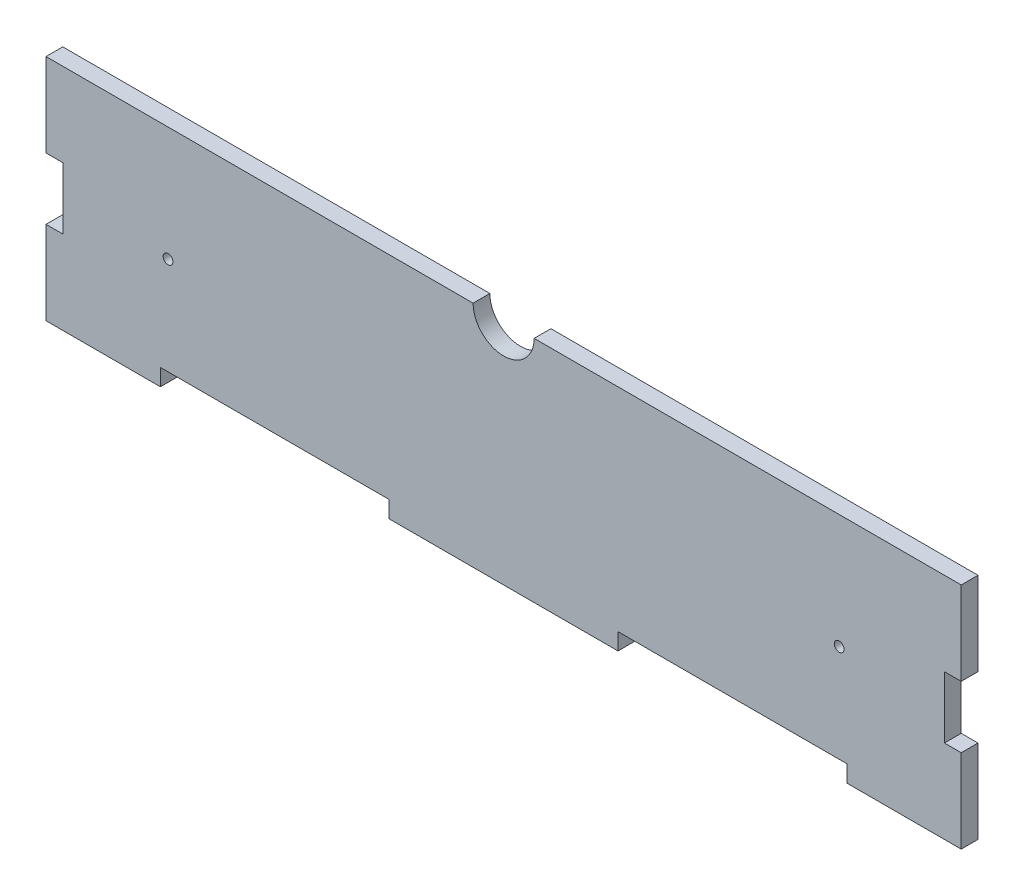
SolidWorks part; units mm, degrees
ref_plane "Front Plane" through (0, 0, 0) normal (0, 0, 1) x (1, 0, 0)
ref_plane "Top Plane" through (0, 0, 0) normal (0, 1, 0) x (1, 0, 0)
ref_plane "Right Plane" through (0, 0, 0) normal (1, 0, 0) x (0, 0, -1)
sketch "Sketch1" plane through (0, 0, 0) normal (0, 0, 1) x (1, 0, 0)
  line L0 (0, 78) -> (0, 50.625)
  line L1 (0, 50.625) -> (5.5, 50.625)
  line L2 (5.5, 50.625) -> (5.5, 42.125)
  line L3 (5.5, 42.125) -> (14.95, 42.125)
  line L4 (14.95, 42.125) -> (14.95, 43.375)
  line L5 (14.95, 43.375) -> (17.6, 43.375)
  line L6 (17.6, 43.375) -> (17.6, 42.125)
  line L7 (17.6, 42.125) -> (20.25, 42.125)
  line L8 (20.25, 42.125) -> (20.25, 38.875)
  line L9 (20.25, 38.875) -> (17.6, 38.875)
  line L10 (17.6, 38.875) -> (17.6, 37.625)
  line L11 (17.6, 37.625) -> (14.95, 37.625)
  line L12 (14.95, 37.625) -> (14.95, 38.875)
  line L13 (14.95, 38.875) -> (5.5, 38.875)
  line L14 (5.5, 38.875) -> (5.5, 30.375)
  line L15 (5.5, 30.375) -> (0, 30.375)
  line L16 (0, 30.375) -> (0, 3)
  line L17 (0, 3) -> (37.5, 3)
  line L18 (37.5, 3) -> (37.5, 8.5)
  line L19 (37.5, 8.5) -> (73.375, 8.5)
  line L20 (73.375, 8.5) -> (73.375, 17.95)
  line L21 (73.375, 17.95) -> (72.125, 17.95)
  line L22 (72.125, 17.95) -> (72.125, 20.6)
  line L23 (72.125, 20.6) -> (73.375, 20.6)
  line L24 (73.375, 20.6) -> (73.375, 23.25)
  line L25 (73.375, 23.25) -> (76.625, 23.25)
  line L26 (76.625, 23.25) -> (76.625, 20.6)
  line L27 (76.625, 20.6) -> (77.875, 20.6)
  line L28 (77.875, 20.6) -> (77.875, 17.95)
  line L29 (77.875, 17.95) -> (76.625, 17.95)
  line L30 (76.625, 17.95) -> (76.625, 8.5)
  line L31 (76.625, 8.5) -> (112.5, 8.5)
  line L32 (112.5, 8.5) -> (112.5, 3)
  line L33 (112.5, 3) -> (187.5, 3)
  line L34 (187.5, 3) -> (187.5, 8.5)
  line L35 (187.5, 8.5) -> (223.375, 8.5)
  line L36 (223.375, 8.5) -> (223.375, 17.95)
  line L37 (223.375, 17.95) -> (222.125, 17.95)
  line L38 (222.125, 17.95) -> (222.125, 20.6)
  line L39 (222.125, 20.6) -> (223.375, 20.6)
  line L40 (223.375, 20.6) -> (223.375, 23.25)
  line L41 (223.375, 23.25) -> (226.625, 23.25)
  line L42 (226.625, 23.25) -> (226.625, 20.6)
  line L43 (226.625, 20.6) -> (227.875, 20.6)
  line L44 (227.875, 20.6) -> (227.875, 17.95)
  line L45 (227.875, 17.95) -> (226.625, 17.95)
  line L46 (226.625, 17.95) -> (226.625, 8.5)
  line L47 (226.625, 8.5) -> (262.5, 8.5)
  line L48 (262.5, 8.5) -> (262.5, 3)
  line L49 (262.5, 3) -> (300, 3)
  line L50 (300, 3) -> (300, 30.375)
  line L51 (300, 30.375) -> (294.5, 30.375)
  line L52 (294.5, 30.375) -> (294.5, 38.875)
  line L53 (294.5, 38.875) -> (285.05, 38.875)
  line L54 (285.05, 38.875) -> (285.05, 37.625)
  line L55 (285.05, 37.625) -> (282.4, 37.625)
  line L56 (282.4, 37.625) -> (282.4, 38.875)
  line L57 (282.4, 38.875) -> (279.75, 38.875)
  line L58 (279.75, 38.875) -> (279.75, 42.125)
  line L59 (279.75, 42.125) -> (282.4, 42.125)
  line L60 (282.4, 42.125) -> (282.4, 43.375)
  line L61 (282.4, 43.375) -> (285.05, 43.375)
  line L62 (285.05, 43.375) -> (285.05, 42.125)
  line L63 (285.05, 42.125) -> (294.5, 42.125)
  line L64 (294.5, 42.125) -> (294.5, 50.625)
  line L65 (294.5, 50.625) -> (300, 50.625)
  line L66 (300, 50.625) -> (300, 78)
  line L67 (300, 78) -> (0, 78)
sketch "Sketch2" plane through (0, 0, 0) normal (0, 0, 1) x (1, 0, 0)
  line L0 (300, 78) -> (0, 78) construction
  circle A0 centre (150, 78) radius 10
  dimension "D1" = 20
extrude "Boss-Extrude1" add sketch "Sketch1" along normal blind 5.5
extrude "Cut-Extrude2" cut sketch "Sketch2" along normal through all
sketch "Sketch3" plane through (0, 0, 5.5) normal (0, 0, 1) x (1, 0, 0)
  line L0 (20.25, 42.125) -> (20.25, 38.875) construction
  line L1 (0, 78) -> (0, 50.625) construction
  line L2 (300, 50.625) -> (300, 78) construction
  circle A0 centre (40, 40.5) radius 1.6
  circle A1 centre (260, 40.5) radius 1.6
  point P7 (20.25, 40.5)
  dimension "D1" = 3.2
  dimension "D2" = 40
  dimension "D3" = 40
extrude "Cut-Extrude3" cut sketch "Sketch3" against normal through all
sketch "Sketch4" plane through (0, 0, 5.5) normal (0, 0, 1) x (1, 0, 0)
  line L0 (282.4, 38.875) -> (279.75, 38.875) construction
  line L1 (5.5, 42.125) -> (20.25, 42.125)
  line L2 (5.5, 42.125) -> (5.5, 38.875)
  line L3 (5.5, 38.875) -> (20.25, 38.875)
  line L4 (20.25, 42.125) -> (20.25, 38.875)
  line L5 (14.95, 43.375) -> (17.6, 43.375)
  line L6 (14.95, 43.375) -> (14.95, 37.625)
  line L7 (14.95, 37.625) -> (17.6, 37.625)
  line L8 (17.6, 43.375) -> (17.6, 37.625)
  line L9 (76.625, 8.5) -> (73.375, 8.5)
  line L10 (76.625, 8.5) -> (76.625, 23.25)
  line L11 (76.625, 23.25) -> (73.375, 23.25)
  line L12 (73.375, 8.5) -> (73.375, 23.25)
  line L13 (77.875, 17.95) -> (72.125, 17.95)
  line L14 (77.875, 17.95) -> (77.875, 20.6)
  line L15 (77.875, 20.6) -> (72.125, 20.6)
  line L16 (72.125, 17.95) -> (72.125, 20.6)
  line L17 (223.375, 8.5) -> (226.625, 8.5)
  line L18 (223.375, 8.5) -> (223.375, 23.25)
  line L19 (223.375, 23.25) -> (226.625, 23.25)
  line L20 (226.625, 8.5) -> (226.625, 23.25)
  line L21 (222.125, 20.6) -> (227.875, 20.6)
  line L22 (222.125, 20.6) -> (222.125, 17.95)
  line L23 (222.125, 17.95) -> (227.875, 17.95)
  line L24 (227.875, 20.6) -> (227.875, 17.95)
  line L25 (294.5, 42.125) -> (279.75, 42.125)
  line L26 (294.5, 42.125) -> (294.5, 38.875)
  line L27 (294.5, 38.875) -> (279.75, 38.875)
  line L28 (279.75, 42.125) -> (279.75, 38.875)
  line L30 (282.4, 43.375) -> (285.05, 43.375)
  line L31 (282.4, 43.375) -> (282.4, 37.625)
  line L32 (282.4, 37.625) -> (285.05, 37.625)
  line L33 (285.05, 43.375) -> (285.05, 37.625)
extrude "Boss-Extrude2" add sketch "Sketch4" against normal up to surface (5.5 mm away) contours L25 L33 L27 L26 | L33 L25 L31 L27 | L31 L25 L28 L27 | L33 L27 L31 L32 | L33 L30 L31 L25 | L23 L18 L17 L20 | L18 L23 L20 L21 | L18 L21 L20 L19 | L24 L21 L20 L23 | L22 L23 L18 L21 | L10 L13 L12 L9 | L10 L15 L12 L13 | L15 L10 L11 L12 | L14 L15 L10 L13 | L16 L13 L12 L15 | L6 L1 L2 L3 | L8 L1 L6 L3 | L8 L3 L6 L7 | L1 L8 L3 L4 | L8 L5 L6 L1 up to face at (41.6, 40.5, 0)
